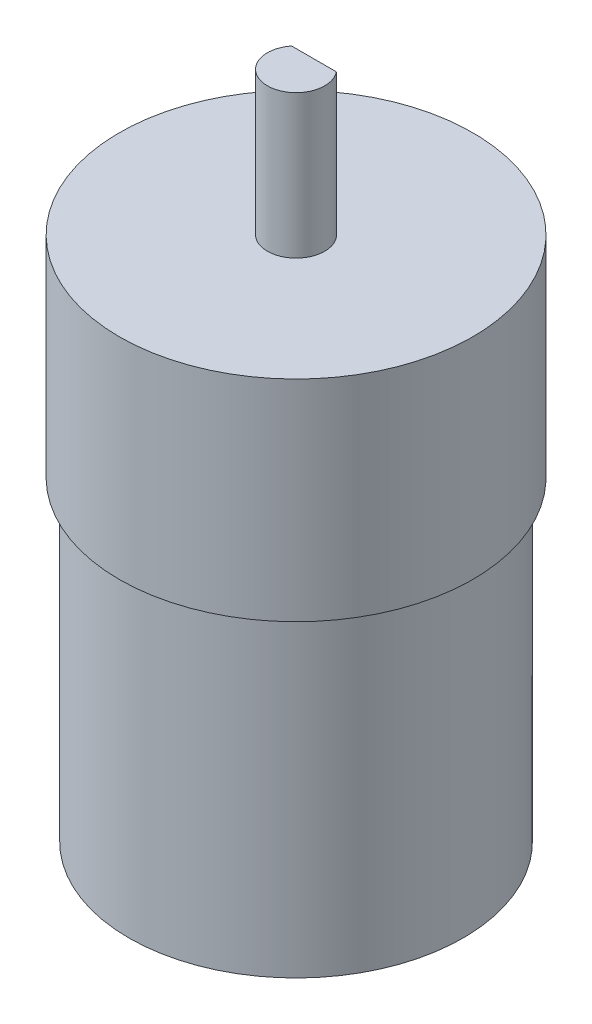
SolidWorks part; units mm, degrees
ref_plane "前视基准面" through (0, 0, 0) normal (0, 0, 1) x (1, 0, 0)
ref_plane "上视基准面" through (0, 0, 0) normal (0, 1, 0) x (1, 0, 0)
ref_plane "右视基准面" through (0, 0, 0) normal (1, 0, 0) x (0, 0, -1)
sketch "草图1" plane through (0, 0, 0) normal (0, 1, 0) x (1, 0, 0)
  circle A0 centre (0, 0) radius 17.5
extrude "凸台-拉伸1" add sketch "草图1" along normal blind 33
sketch "草图2" plane through (0, 33, 0) normal (0, 1, 0) x (1, 0, 0)
  circle A0 centre (0, 0) radius 18.5
extrude "凸台-拉伸2" add sketch "草图2" along normal blind 22
sketch "草图3" plane through (0, 55, 0) normal (0, 1, 0) x (1, 0, 0)
  line L0 (0, 1.8779) -> (-2.3395, 1.8779)
  line L1 (0, 1.8779) -> (2.3395, 1.8779)
  circle A0 centre (0, 0) radius 3
extrude "凸台-拉伸3" add sketch "草图3" along normal blind 15 contours L0 A0 L1
